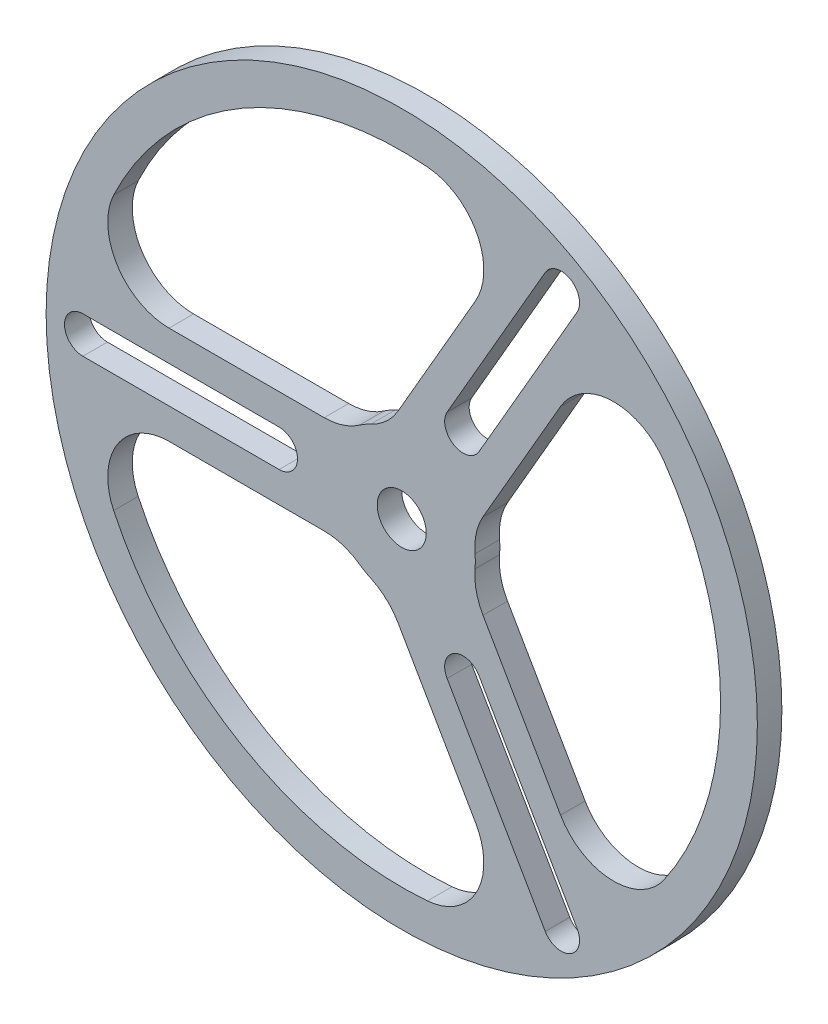
SolidWorks part; units mm, degrees
ref_plane "前视基准面" through (0, 0, 0) normal (0, 0, 1) x (1, 0, 0)
ref_plane "上视基准面" through (0, 0, 0) normal (0, 1, 0) x (1, 0, 0)
ref_plane "右视基准面" through (0, 0, 0) normal (1, 0, 0) x (0, 0, -1)
sketch "草图1" plane through (0, 0, 0) normal (0, 0, 1) x (1, 0, 0)
  line L0 (31.691, 0) -> (-35.4567, 0) construction
  line L1 (0, -33.0697) -> (0, 40.8478) construction
  line L2 (-10, 0) -> (-26, 0) construction
  line L3 (-10, -1.5) -> (-26, -1.5)
  line L4 (-10, 1.5) -> (-26, 1.5)
  line L5 (5, 8.6603) -> (13, 22.5167) construction
  line L6 (3.701, 9.4103) -> (11.701, 23.2667)
  line L7 (6.299, 7.9103) -> (14.299, 21.7667)
  line L8 (5, -8.6603) -> (13, -22.5167) construction
  line L9 (6.299, -7.9103) -> (14.299, -21.7667)
  line L10 (3.701, -9.4103) -> (11.701, -23.2667)
  circle A0 centre (0, 0) radius 29
  arc A1 (-10, -1.5) -> (-10, 1.5) centre (-10, 0) ccw
  arc A2 (-26, 1.5) -> (-26, -1.5) centre (-26, 0) ccw
  circle A3 centre (0, 0) radius 2
  arc A4 (3.701, 9.4103) -> (6.299, 7.9103) centre (5, 8.6603) ccw
  arc A5 (14.299, 21.7667) -> (11.701, 23.2667) centre (13, 22.5167) ccw
  arc A6 (6.299, -7.9103) -> (3.701, -9.4103) centre (5, -8.6603) ccw
  arc A7 (11.701, -23.2667) -> (14.299, -21.7667) centre (13, -22.5167) ccw
  point P9 (-18, 0)
  point P20 (9, 15.5885)
  point P27 (9, -15.5885)
  point P32 (0, 0)
  dimension "D1" = 58
  dimension "D2" = 4
  dimension "D3" = 1.5
  dimension "D4" = 26
  dimension "D5" = 10
  dimension "D6" = 3
extrude "凸台-拉伸1" add sketch "草图1" along normal blind 2
sketch "草图2" plane through (0, 0, 2) normal (0, 0, 1) x (1, 0, 0)
  line L0 (-34.4003, 0) -> (39.4324, 0) construction
  line L1 (0, 0) -> (17.146, 29.6978) construction
  line L2 (-18.9737, 4) -> (-6.3246, 4)
  line L3 (-18.9737, -4) -> (-6.3246, -4)
  line L4 (12.9509, 14.4317) -> (6.6264, 3.4772)
  line L5 (6.0227, 18.4317) -> (-0.3018, 7.4772)
  line L6 (6.0227, -18.4317) -> (-0.3018, -7.4772)
  line L7 (12.9509, -14.4317) -> (6.6264, -3.4772)
  arc A0 (-23.4912, -11.1429) -> (2.0956, -25.9154) centre (0, 0) ccw
  arc A1 (-2.5265, 5.4421) -> (-3.4498, 4.9091) centre (0, 0) ccw
  arc A2 (-23.4912, 11.1429) -> (-18.9737, 4) centre (-18.9737, 9) ccw
  arc A3 (-6.3246, 4) -> (-3.4498, 4.9091) centre (-6.3246, 9) ccw
  arc A4 (-6.3246, -4) -> (-3.4498, -4.9091) centre (-6.3246, -9) cw
  arc A5 (-23.4912, -11.1429) -> (-18.9737, -4) centre (-18.9737, -9) cw
  arc A6 (21.3956, 14.7726) -> (12.9509, 14.4317) centre (17.2811, 11.9317) ccw
  arc A7 (6.6264, 3.4772) -> (5.9763, 0.533) centre (10.9565, 0.9772) ccw
  arc A8 (2.0956, 25.9154) -> (6.0227, 18.4317) centre (1.6926, 20.9317) cw
  arc A9 (-0.3018, 7.4772) -> (-2.5265, 5.4421) centre (-4.632, 9.9772) cw
  arc A10 (2.0956, -25.9154) -> (6.0227, -18.4317) centre (1.6926, -20.9317) ccw
  arc A11 (-0.3018, -7.4772) -> (-2.5265, -5.4421) centre (-4.632, -9.9772) ccw
  arc A12 (21.3956, -14.7726) -> (12.9509, -14.4317) centre (17.2811, -11.9317) cw
  arc A13 (6.6264, -3.4772) -> (5.9763, -0.533) centre (10.9565, -0.9772) cw
  arc A14 (2.0956, 25.9154) -> (-23.4912, 11.1429) centre (0, 0) ccw
  arc A15 (5.9763, -0.533) -> (5.9763, 0.533) centre (0, 0) ccw
  arc A16 (21.3956, -14.7726) -> (21.3956, 14.7726) centre (0, 0) ccw
  arc A17 (-3.4498, -4.9091) -> (-2.5265, -5.4421) centre (0, 0) ccw
  point P45 (0, 0)
  dimension "D1" = 52
  dimension "D2" = 12
  dimension "D4" = 10
  dimension "D5" = 10
  dimension "D6" = 3
  dimension "D3" = 8
extrude "切除-拉伸1" cut sketch "草图2" against normal blind 2
